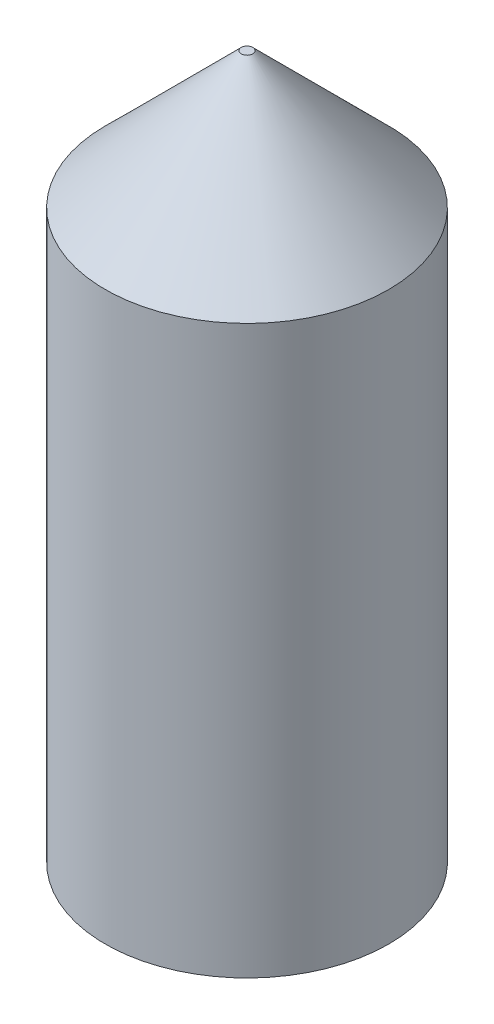
SolidWorks part; units mm, degrees
material "Plain Carbon Steel"
ref_plane "Front Plane" through (0, 0, 0) normal (0, 0, 1) x (1, 0, 0)
ref_plane "Top Plane" through (0, 0, 0) normal (0, 1, 0) x (1, 0, 0)
ref_plane "Right Plane" through (0, 0, 0) normal (1, 0, 0) x (0, 0, -1)
sketch "Sketch1" plane through (0, 0, 0) normal (0, 0, 1) x (1, 0, 0)
  line L2 (2.5, 0) -> (0, 0)
  line L3 (0, 2.4) -> (0, 0)
  line L4 (0, -76.0931) -> (0, 3728.5618) construction
  line L5 (0, 2.4) -> (0.1, 2.4)
  line L6 (0.1, 2.4) -> (2.5, 0)
  dimension "D1" = 5
  dimension "D2" = 0.2
  dimension "D3" = 45
revolve "Revolve1" add sketch "Sketch1" angle 360 about L4
sketch "Sketch2" plane through (0, 0, 0) normal (0, -1, 0) x (1, 0, 0)
  circle A0 centre (0, 0) radius 2.5 construction
  circle A1 centre (0, 0) radius 2.5
extrude "Boss-Extrude1" add sketch "Sketch2" along normal blind 10
